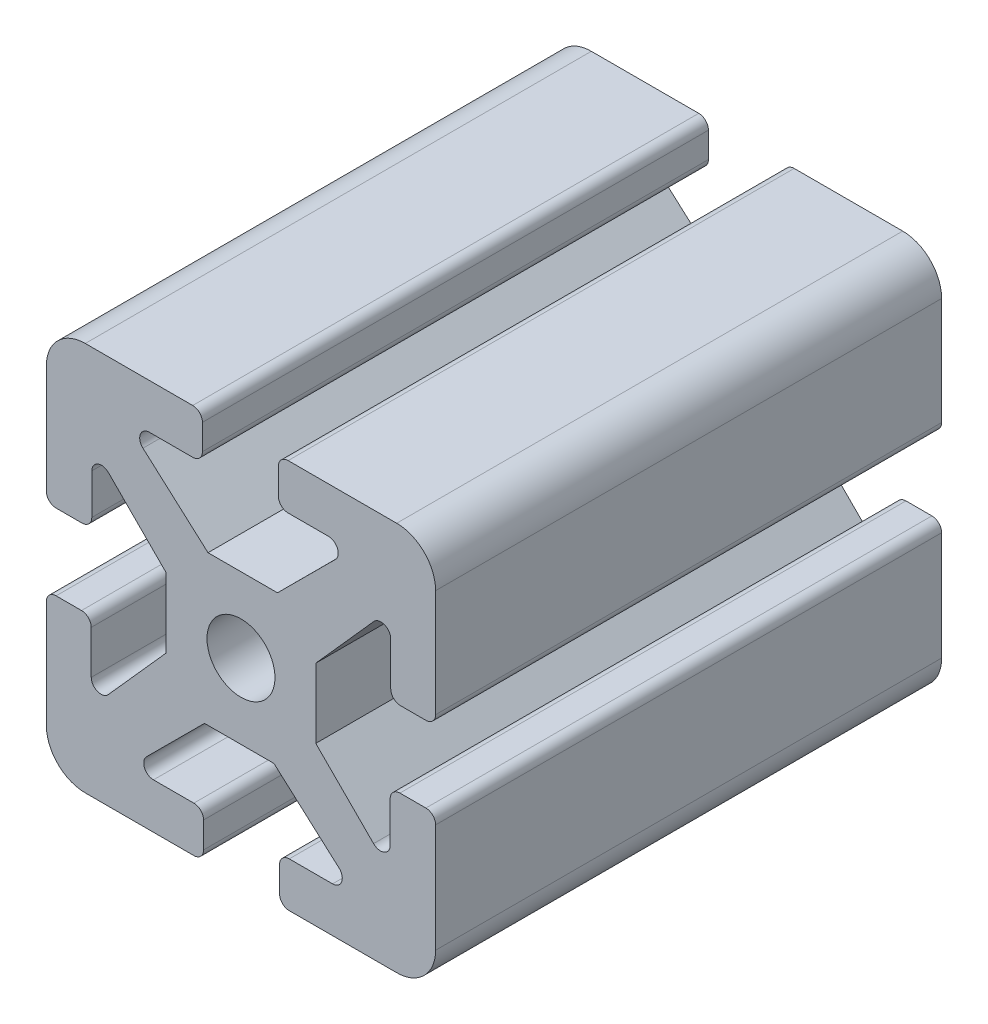
SolidWorks part; units mm, degrees
ref_plane "Front Plane" through (0, 0, 0) normal (0, 0, 1) x (1, 0, 0)
ref_plane "Top Plane" through (0, 0, 0) normal (0, 1, 0) x (1, 0, 0)
ref_plane "Right Plane" through (0, 0, 0) normal (1, 0, 0) x (0, 0, -1)
sketch "Sketch2" plane through (0, 0, 0) normal (0, 0, 1) x (1, 0, 0)
  line L0 (46.607, 139.3199) -> (233.0351, 139.3199) construction
  line L1 (0, 40) -> (40, 0) construction
  line L2 (0, 0) -> (40, 0) construction
  line L3 (0, 0) -> (0, 40) construction
  line L4 (0, 40) -> (40, 40) construction
  line L5 (40, 0) -> (40, 40) construction
  line L6 (0, 0) -> (40, 40) construction
  line L7 (19.4883, 27.6847) -> (23.7499, 27.6847)
  line L8 (23.7499, 27.6847) -> (29.6997, 33.625)
  line L9 (28.9931, 35.3327) -> (24.8456, 35.3327)
  line L10 (23.8456, 36.3327) -> (23.8456, 39)
  line L11 (24.8456, 40) -> (36, 40)
  line L12 (40, 36) -> (40, 24.9611)
  line L13 (39, 23.9611) -> (36.3883, 23.9611)
  line L14 (35.3883, 24.9611) -> (35.3883, 29.4086)
  line L15 (33.6417, 30.0739) -> (27.6847, 23.3888)
  line L16 (27.6847, 23.3888) -> (27.6847, 20.5117)
  line L17 (27.6847, 16.2501) -> (33.625, 10.3003)
  line L18 (30.0739, 6.3583) -> (23.3888, 12.3153)
  line L19 (27.6847, 20.5117) -> (27.6847, 16.2501)
  line L20 (35.3327, 11.0069) -> (35.3327, 15.1544)
  line L21 (36.3327, 16.1544) -> (39, 16.1544)
  line L22 (40, 15.1544) -> (40, 4)
  line L23 (36, 0) -> (24.9611, 0)
  line L24 (23.9611, 1) -> (23.9611, 3.6117)
  line L25 (24.9611, 4.6117) -> (29.4086, 4.6117)
  line L26 (23.3888, 12.3153) -> (20.5117, 12.3153)
  line L27 (16.2501, 12.3153) -> (10.3003, 6.375)
  line L28 (6.3583, 9.9261) -> (12.3153, 16.6112)
  line L29 (20.5117, 12.3153) -> (16.2501, 12.3153)
  line L30 (11.0069, 4.6673) -> (15.1544, 4.6673)
  line L31 (16.1544, 3.6673) -> (16.1544, 1)
  line L32 (15.1544, 0) -> (4, 0)
  line L33 (0, 4) -> (0, 15.0389)
  line L34 (1, 16.0389) -> (3.6117, 16.0389)
  line L35 (4.6117, 15.0389) -> (4.6117, 10.5914)
  line L36 (12.3153, 16.6112) -> (12.3153, 19.4883)
  line L37 (12.3153, 23.7499) -> (6.375, 29.6997)
  line L38 (9.9261, 33.6417) -> (16.6112, 27.6847)
  line L39 (12.3153, 19.4883) -> (12.3153, 23.7499)
  line L40 (4.6673, 28.9931) -> (4.6673, 24.8456)
  line L41 (3.6673, 23.8456) -> (1, 23.8456)
  line L42 (0, 24.8456) -> (0, 36)
  line L43 (4, 40) -> (15.0389, 40)
  line L44 (16.0389, 39) -> (16.0389, 36.3883)
  line L45 (15.0389, 35.3883) -> (10.5914, 35.3883)
  line L46 (16.6112, 27.6847) -> (19.4883, 27.6847)
  circle A1 centre (20, 20) radius 3.4925
  arc A2 (40, 24.9611) -> (39, 23.9611) centre (39, 24.9611) cw
  arc A3 (36.3883, 23.9611) -> (35.3883, 24.9611) centre (36.3883, 24.9611) cw
  arc A4 (24.8456, 35.3327) -> (23.8456, 36.3327) centre (24.8456, 36.3327) cw
  arc A5 (23.8456, 39) -> (24.8456, 40) centre (24.8456, 39) cw
  arc A6 (29.6997, 33.625) -> (28.9931, 35.3327) centre (28.9931, 34.3327) ccw
  arc A7 (35.3883, 29.4086) -> (33.6417, 30.0739) centre (34.3883, 29.4086) ccw
  arc A8 (40, 36) -> (36, 40) centre (36, 36) ccw
  arc A9 (35.3327, 15.1544) -> (36.3327, 16.1544) centre (36.3327, 15.1544) cw
  arc A10 (39, 16.1544) -> (40, 15.1544) centre (39, 15.1544) cw
  arc A11 (36, 0) -> (40, 4) centre (36, 4) ccw
  arc A12 (24.9611, 0) -> (23.9611, 1) centre (24.9611, 1) cw
  arc A13 (23.9611, 3.6117) -> (24.9611, 4.6117) centre (24.9611, 3.6117) cw
  arc A14 (29.4086, 4.6117) -> (30.0739, 6.3583) centre (29.4086, 5.6117) ccw
  arc A15 (33.625, 10.3003) -> (35.3327, 11.0069) centre (34.3327, 11.0069) ccw
  arc A16 (15.1544, 4.6673) -> (16.1544, 3.6673) centre (15.1544, 3.6673) cw
  arc A17 (16.1544, 1) -> (15.1544, 0) centre (15.1544, 1) cw
  arc A18 (0, 4) -> (4, 0) centre (4, 4) ccw
  arc A19 (0, 15.0389) -> (1, 16.0389) centre (1, 15.0389) cw
  arc A20 (3.6117, 16.0389) -> (4.6117, 15.0389) centre (3.6117, 15.0389) cw
  arc A21 (4.6117, 10.5914) -> (6.3583, 9.9261) centre (5.6117, 10.5914) ccw
  arc A22 (10.3003, 6.375) -> (11.0069, 4.6673) centre (11.0069, 5.6673) ccw
  arc A23 (4.6673, 24.8456) -> (3.6673, 23.8456) centre (3.6673, 24.8456) cw
  arc A24 (1, 23.8456) -> (0, 24.8456) centre (1, 24.8456) cw
  arc A25 (4, 40) -> (0, 36) centre (4, 36) ccw
  arc A26 (15.0389, 40) -> (16.0389, 39) centre (15.0389, 39) cw
  arc A27 (16.0389, 36.3883) -> (15.0389, 35.3883) centre (15.0389, 36.3883) cw
  arc A28 (10.5914, 35.3883) -> (9.9261, 33.6417) centre (10.5914, 34.3883) ccw
  arc A29 (6.375, 29.6997) -> (4.6673, 28.9931) centre (5.6673, 28.9931) ccw
  point P24 (40, 23.9611)
  point P31 (23.8456, 40)
  dimension "D1" = 40
  dimension "D3" = 1
  dimension "D4" = 4
  dimension "D2" = 40
  dimension "D5" = 4
extrude "Boss-Extrude1" add sketch "Sketch2" along normal blind 52
